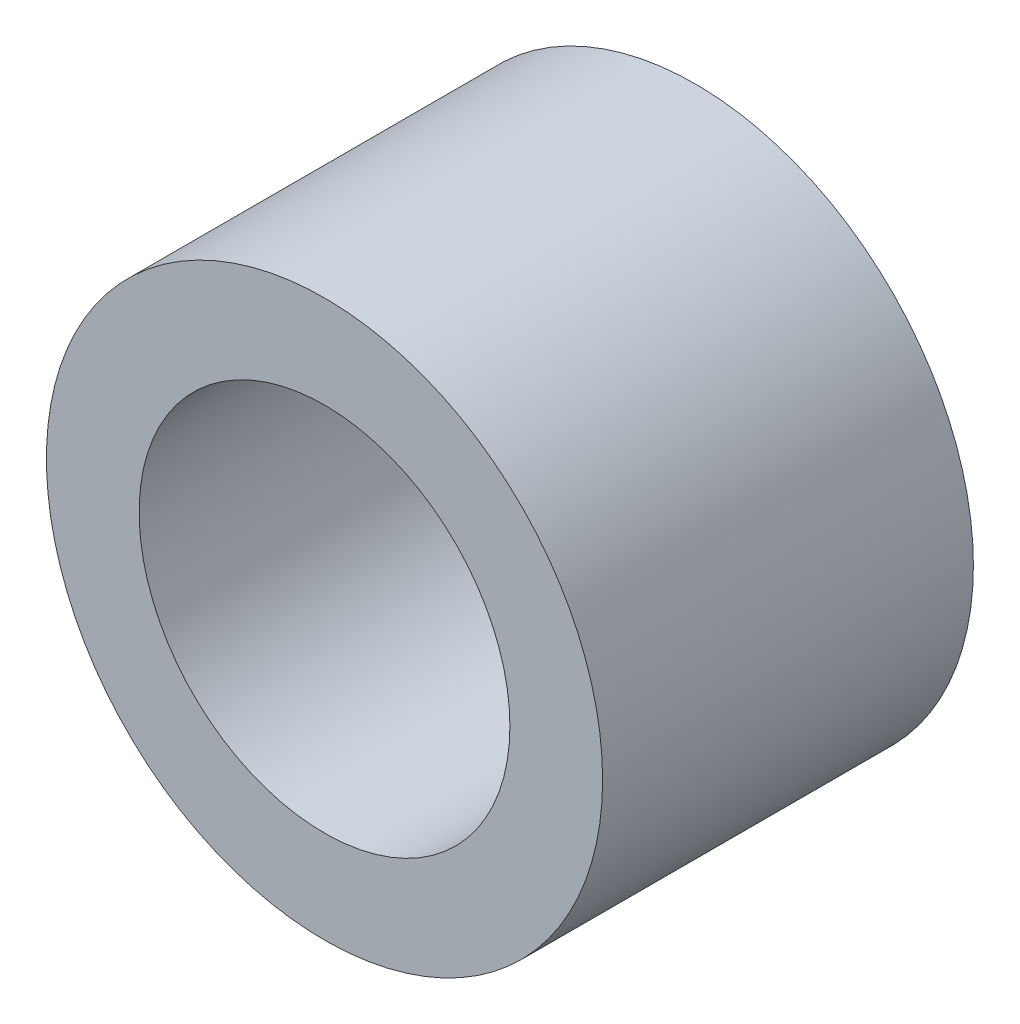
SolidWorks part; units mm, degrees
ref_plane "Front Plane" through (0, 0, 0) normal (0, 0, 1) x (1, 0, 0)
ref_plane "Top Plane" through (0, 0, 0) normal (0, 1, 0) x (1, 0, 0)
ref_plane "Right Plane" through (0, 0, 0) normal (1, 0, 0) x (0, 0, -1)
sketch "Sketch1" plane through (0, 0, 0) normal (0, 0, 1) x (1, 0, 0)
  circle A0 centre (0, 0) radius 4.7625
  circle A1 centre (0, 0) radius 3.175
  dimension "D1" = 9.525
  dimension "ID" = 6.35
extrude "Extrude1" add sketch "Sketch1" along normal mid plane 6.35
sketch "Sketch2" plane through (0, 0, 0) normal (1, 0, 0) x (0, 0, -1)
  line L0 (-3.175, -3.175) -> (3.175, -3.175) construction
  line L3 (3.175, 3.175) -> (-3.175, 3.175) construction
  line L5 (-3.175, -3.175) -> (3.175, -3.175)
  line L6 (3.175, 3.175) -> (-3.175, 3.175)
sketch "Sketch4" plane through (0, 0, 3.175) normal (0, 0, 1) x (1, 0, 0)
  line L0 (0, 0) -> (-2.2451, 2.2451)
  line L1 (0, -24.4475) -> (0, 24.4475) construction
  circle A0 centre (0, 0) radius 3.175 construction
  dimension "D1" = 45
